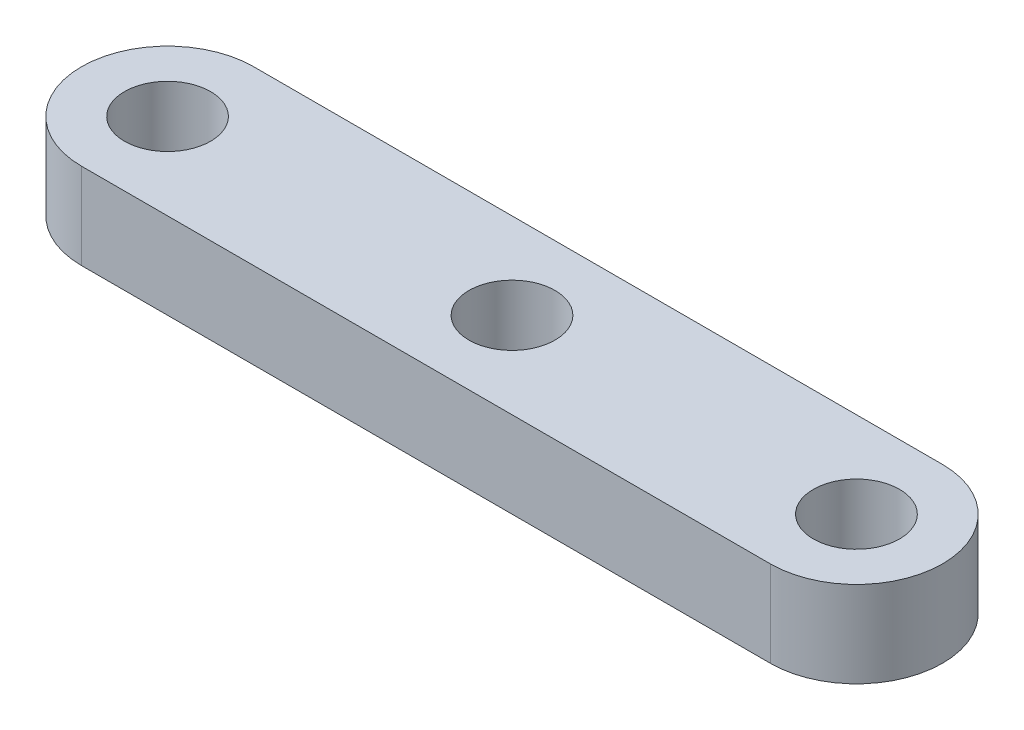
SolidWorks part; units mm, degrees
ref_plane "Front" through (0, 0, 0) normal (0, 0, 1) x (1, 0, 0)
ref_plane "Top" through (0, 0, 0) normal (0, 1, 0) x (1, 0, 0)
ref_plane "Right" through (0, 0, 0) normal (1, 0, 0) x (0, 0, -1)
sketch "Sketch1" plane through (0, 0, 0) normal (0, 1, 0) x (1, 0, 0)
  line L1 (-20, -5) -> (20, -5)
  line L2 (-20, -5) -> (-20, 5) construction
  line L3 (-20, 5) -> (20, 5)
  line L4 (20, -5) -> (20, 5) construction
  line L5 (-20, -5) -> (20, 5) construction
  line L6 (-20, 5) -> (20, -5) construction
  arc A0 (-20, 5) -> (-20, -5) centre (-20, 0) ccw
  arc A1 (20, 5) -> (20, -5) centre (20, 0) cw
  point P0 (0, 0)
  dimension "D1" = 10
  dimension "D2" = 40
extrude "Boss-Extrude1" add sketch "Sketch1" along normal blind 5
sketch "Sketch2" plane through (0, 5, 0) normal (0, 1, 0) x (1, 0, 0)
  circle A0 centre (-20, 0) radius 2.5
  circle A1 centre (20, 0) radius 2.5
  circle A2 centre (0, 0) radius 2.5
  dimension "D1" = 5
  dimension "D2" = 20
extrude "Cut-Extrude1" cut sketch "Sketch2" against normal through all
